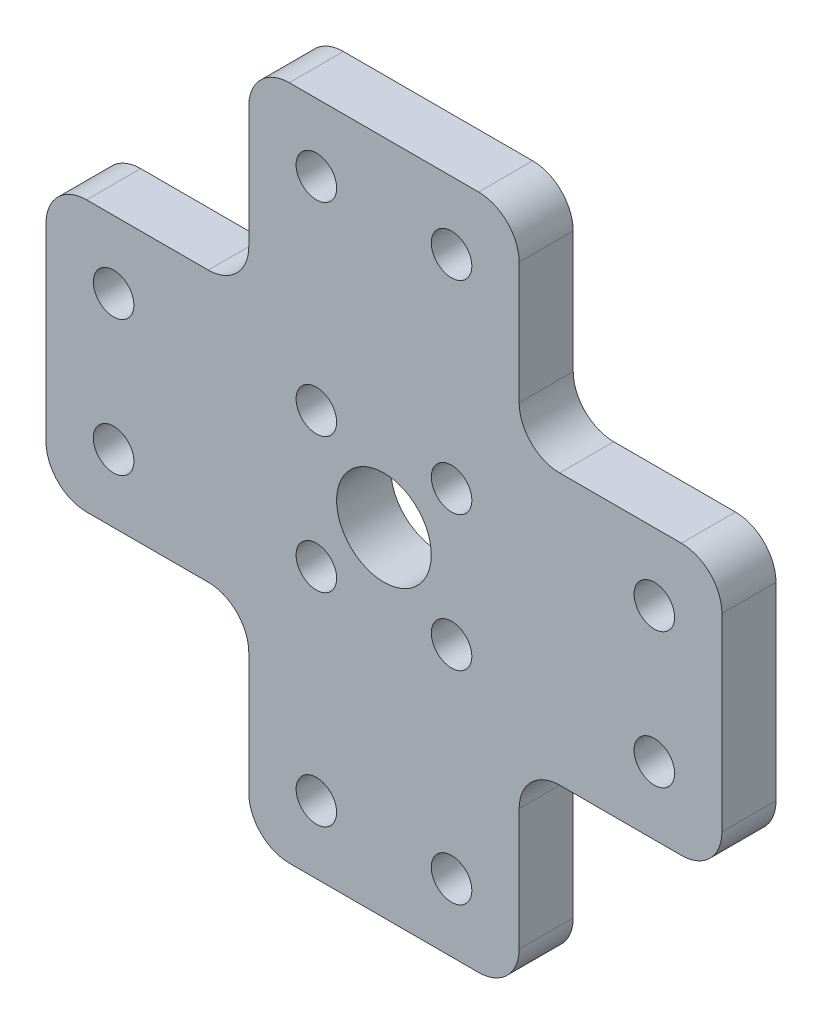
SolidWorks part; units mm, degrees
material "Thornel Mat VMA"
ref_plane "前视基准面" through (0, 0, 0) normal (0, 0, 1) x (1, 0, 0)
ref_plane "上视基准面" through (0, 0, 0) normal (0, 1, 0) x (1, 0, 0)
ref_plane "右视基准面" through (0, 0, 0) normal (1, 0, 0) x (0, 0, -1)
other "Configuration Table"
sketch "草图1" plane through (0, 0, 0) normal (0, 0, 1) x (1, 0, 0)
  line L1 (-25, 10) -> (25, 10)
  line L2 (-25, 10) -> (-25, -10)
  line L3 (-25, -10) -> (25, -10)
  line L4 (25, 10) -> (25, -10)
  line L5 (-25, 10) -> (25, -10) construction
  line L6 (-25, -10) -> (25, 10) construction
  line L7 (-10, 25) -> (10, 25)
  line L8 (-10, 25) -> (-10, -25)
  line L9 (-10, -25) -> (10, -25)
  line L10 (10, 25) -> (10, -25)
  line L11 (-10, 25) -> (10, -25) construction
  line L12 (-10, -25) -> (10, 25) construction
  circle A0 centre (-20, -5) radius 1.5
  circle A1 centre (20, -5) radius 1.5
  circle A2 centre (20, 5) radius 1.5
  circle A3 centre (-20, 5) radius 1.5
  circle A4 centre (-5, -5) radius 1.5
  circle A5 centre (5, -5) radius 1.5
  circle A6 centre (5, 5) radius 1.5
  circle A7 centre (-5, 5) radius 1.5
  circle A8 centre (5, -20) radius 1.5
  circle A9 centre (-5, -20) radius 1.5
  circle A10 centre (-5, 20) radius 1.5
  circle A11 centre (5, 20) radius 1.5
  circle A12 centre (0, 0) radius 3.5
  point P0 (0, 0)
  point P6 (0, 0)
  dimension "D9" = 3
  dimension "D10" = 2
  dimension "D12" = 5
  dimension "D13" = 5
  dimension "D14" = 5
  dimension "D16" = 5
  dimension "D17" = 5
  dimension "D18" = 5
  dimension "D1" = 20
  dimension "D2" = 20
  dimension "D3" = 50
  dimension "D4" = 50
  dimension "D5" = 2
  dimension "D6" = 2
  dimension "D7" = 2
  dimension "D8" = 2
  dimension "D11" = 2
extrude "凸台-拉伸1" add sketch "草图1" along normal blind 4 contours L1 L10 L3 L4 A2 A1 | L10 L1 L8 L3 A7 A6 A5 A4 | L10 L7 L8 L1 A11 A10 | L8 L1 L2 L3 A3 A0 | L10 L3 L8 L9 A9 A8
fillet "圆角1" radius 3 12 edges at (25, 10, 2) (25, -10, 2) (10, -10, 2) (10, -25, 2) (-10, -25, 2) (-10, -10, 2) (-25, -10, 2) (-25, 10, 2) (-10, 10, 2) (-10, 25, 2) (10, 25, 2) (10, 10, 2)
